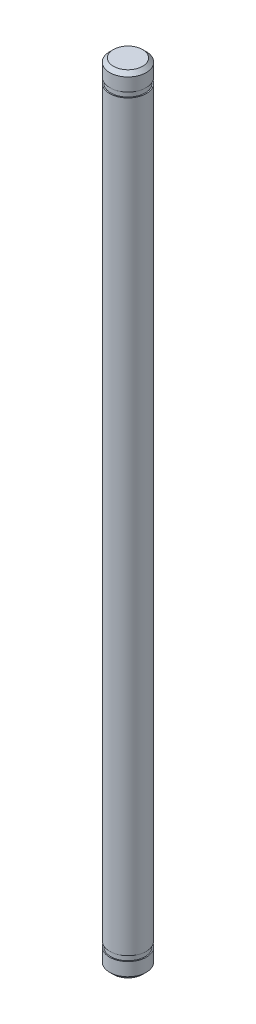
SolidWorks part; units mm, degrees
ref_plane "前视基准面" through (0, 0, 0) normal (0, 0, 1) x (1, 0, 0)
ref_plane "上视基准面" through (0, 0, 0) normal (0, 1, 0) x (1, 0, 0)
ref_plane "右视基准面" through (0, 0, 0) normal (1, 0, 0) x (0, 0, -1)
other "Configuration Table"
sketch "草图1" plane through (0, 0, 0) normal (0, 1, 0) x (1, 0, 0)
  circle A0 centre (0, 0) radius 2.5
  dimension "D1" = 5
extrude "凸台-拉伸1" add sketch "草图1" along normal blind 108
chamfer "倒角1" distance 0.5 angle 45 2 edges at (0, 0, 2.5) (0, 108, 2.5)
ref_plane "基准面1" through (0, 54, 0) normal (0, 1, 0) x (1, 0, 0)
sketch "草图2" plane through (0, 108, 0) normal (0, 1, 0) x (1, 0, 0)
  circle A0 centre (0, 0) radius 2.5 construction
  circle A1 centre (0, 0) radius 2.5
  circle A2 centre (0, 0) radius 2.35
  dimension "D1" = 4.7
extrude "切除-拉伸1" cut sketch "草图2" along normal blind 0.7 from offset 3 offset against normal yes
mirror "镜向1" about plane through (0, 54, 0) normal (0, 1, 0) of "切除-拉伸1"
